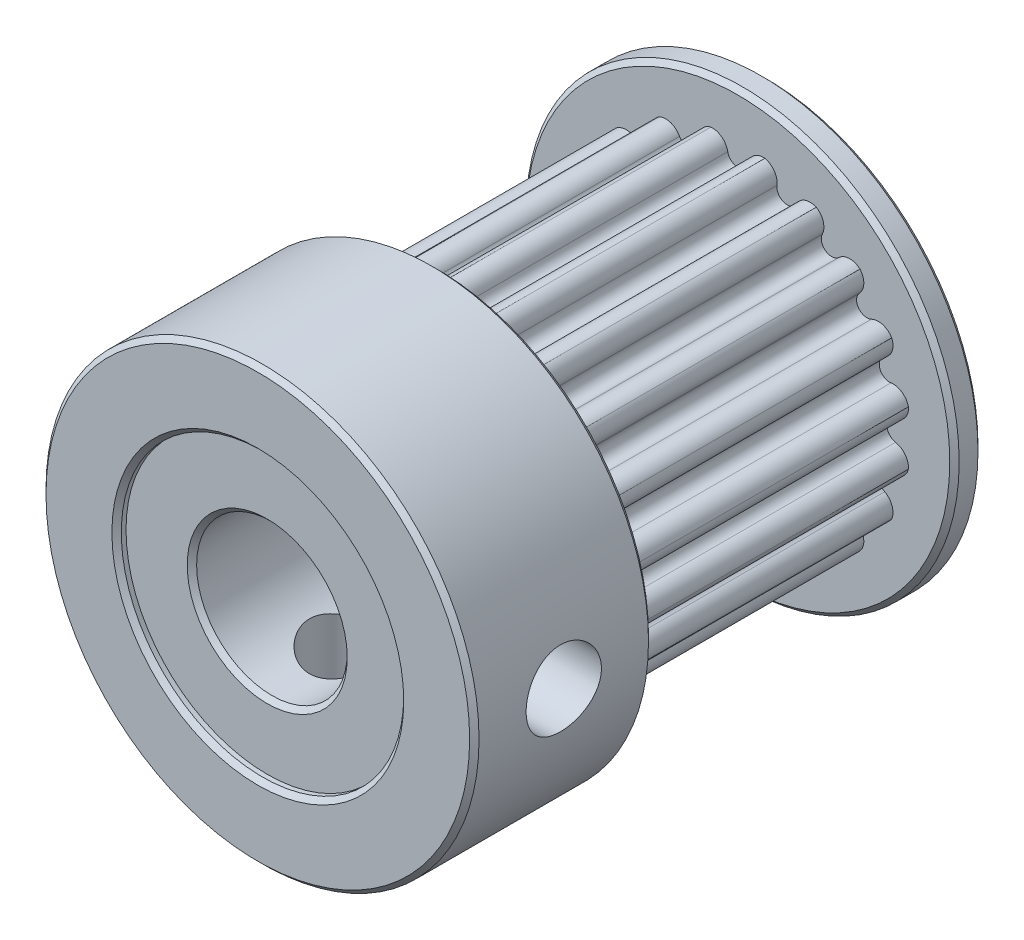
SolidWorks part; units mm, degrees
ref_plane "Plan de face" through (0, 0, 0) normal (0, 0, 1) x (1, 0, 0)
ref_plane "Plan de dessus" through (0, 0, 0) normal (0, 1, 0) x (1, 0, 0)
ref_plane "Plan de droite" through (0, 0, 0) normal (1, 0, 0) x (0, 0, -1)
sketch "Esquisse1" plane through (0, 0, 0) normal (0, 0, 1) x (1, 0, 0)
  circle A0 centre (0, 0) radius 11.5
  circle A1 centre (0, 0) radius 4
  dimension "D1" = 23
  dimension "D2" = 8
extrude "Boss.-Extru.1" add sketch "Esquisse1" along normal blind 27
ref_plane "Plan1" through (0, 0, 1.5) normal (0, 0, -1) x (-1, 0, 0)
sketch "Esquisse2" plane through (0, 0, 1.5) normal (0, 0, -1) x (-1, 0, 0)
  circle A0 centre (0, 0) radius 9.17
  circle A1 centre (0, 0) radius 11.5
  dimension "D1" = 18.34
extrude "Enlèv. mat.-Extru.1" cut sketch "Esquisse2" against normal blind 16
sketch "Esquisse3" plane through (0, 0, 17.5) normal (0, 0, -1) x (-1, 0, 0)
  line L0 (-10.9902, 9.17) -> (15.4189, 9.17) construction
  line L1 (0, 0) -> (0, 15.6348) construction
  line L2 (-1.0417, 7.92) -> (1.5586, 7.92) construction
  circle A0 centre (0, 0) radius 9.17 construction
  circle A1 centre (0, 0) radius 9.17 construction
  arc A2 (-1.5, 9.0465) -> (-0.5411, 8.3716) centre (-1.3633, 8.2221) cw
  arc A3 (-0.5411, 8.3716) -> (0.5411, 8.3716) centre (0, 8.47) ccw
  arc A4 (0.5411, 8.3716) -> (1.5, 9.0465) centre (1.3633, 8.2221) cw
  arc A5 (-1.5, 9.0465) -> (1.5, 9.0465) centre (0, 0) cw
  point P17 (0, 0)
  dimension "D2" = 0.55
  dimension "D1" = 1.25
  dimension "D3" = 3
extrude "Enlèv. mat.-Extru.2" cut sketch "Esquisse3" along normal up to surface (16 mm away) up to face at (-9.17, 0, 1.5)
pattern_circular "Répétition circulaire1" count 20 over 360 about axis through (0, 0, 0) along (0, 0, 1) of "Enlèv. mat.-Extru.2"
sketch "Esquisse4" plane through (0, 0, 0) normal (0, 1, 0) x (1, 0, 0)
  line L0 (0, 0) -> (0, -26.9226) construction
  line L3 (-11.5, -17.5) -> (17.9359, -17.5) construction
  line L4 (17.9359, -17.5) -> (17.9359, -27) construction
  line L5 (17.9359, -27) -> (-11.5, -27) construction
  line L6 (-11.5, -27) -> (11.5, -27) construction
  line L7 (0, -22.25) -> (29.4359, -22.25) construction
  circle A0 centre (0, -22.25) radius 2
  dimension "D1" = 4
extrude "Enlèv. mat.-Extru.3" cut sketch "Esquisse4" against normal blind 16
pattern_circular "Répétition circulaire2" count 2 over 90 about axis through (0, 0, 27) along (0, 0, -1) of "Enlèv. mat.-Extru.3"
sketch "Esquisse5" plane through (0, 0, 0) normal (0, 0, -1) x (-1, 0, 0)
  circle A0 centre (0, 0) radius 7.5
  dimension "D1" = 15
extrude "Enlèv. mat.-Extru.4" cut sketch "Esquisse5" against normal blind 0.5
ref_plane "Plan2" through (0, 0, 13.5) normal (0, 0, -1) x (-1, 0, 0)
mirror "Symétrie1" about plane through (0, 0, 13.5) normal (0, 0, -1) of "Enlèv. mat.-Extru.4"
chamfer "Chanfrein1" distance 0.25 angle 45 8 edges at (4, 0, 26.5) (-4, 0, 0.5) (-7.5, 0, 0) (11.5, 0, 0) (11.5, 0, 27) (-11.5, 0, 17.5) (-11.5, 0, 1.5) (-7.5, 0, 27)
